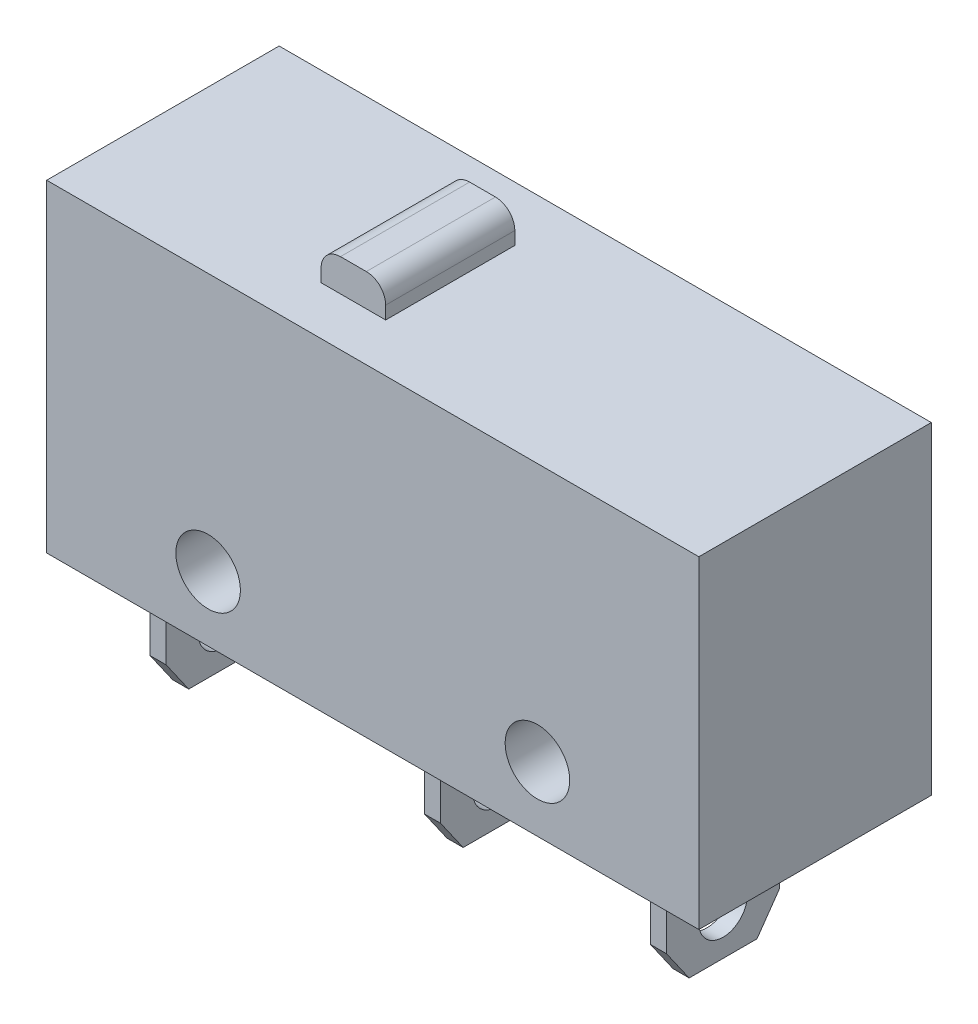
SolidWorks part; units mm, degrees
ref_plane "Спереди" through (0, 0, 0) normal (0, 0, 1) x (1, 0, 0)
ref_plane "Сверху" through (0, 0, 0) normal (0, 1, 0) x (1, 0, 0)
ref_plane "Справа" through (0, 0, 0) normal (1, 0, 0) x (0, 0, -1)
sketch "Эскиз1" plane through (0, 0, 0) normal (0, 1, 0) x (1, 0, 0)
  line L1 (-10.1, 3.6) -> (10.1, 3.6)
  line L2 (-10.1, 3.6) -> (-10.1, -3.6)
  line L3 (-10.1, -3.6) -> (10.1, -3.6)
  line L4 (10.1, 3.6) -> (10.1, -3.6)
  line L5 (-10.1, 3.6) -> (10.1, -3.6) construction
  line L6 (-10.1, -3.6) -> (10.1, 3.6) construction
  point P0 (0, 0)
  dimension "D1" = 20.2
  dimension "D2" = 7.2
extrude "Бобышка-Вытянуть1" add sketch "Эскиз1" along normal blind 10
sketch "Эскиз2" plane through (0, 0, 0) normal (0, -1, 0) x (-1, 0, 0)
  line L0 (-6.75, -1.75) -> (-6.75, 1.75)
  line L1 (0.25, -1.75) -> (-0.25, -1.75)
  line L2 (0.25, -1.75) -> (0.25, 1.75)
  line L3 (0.25, 1.75) -> (-0.25, 1.75)
  line L4 (-0.25, -1.75) -> (-0.25, 1.75)
  line L5 (0.25, -1.75) -> (-0.25, 1.75) construction
  line L6 (0.25, 1.75) -> (-0.25, -1.75) construction
  line L7 (-7.25, -1.75) -> (-7.25, 1.75)
  line L8 (-6.75, -1.75) -> (-7.25, -1.75)
  line L9 (-6.75, 1.75) -> (-7.25, 1.75)
  line L10 (8.75, -1.75) -> (8.75, 1.75)
  line L11 (8.75, -1.75) -> (8.25, -1.75)
  line L12 (8.25, -1.75) -> (8.25, 1.75)
  line L13 (8.75, 1.75) -> (8.25, 1.75)
  point P0 (0, 0)
  dimension "D1" = 3.5
  dimension "D2" = 0.5
  dimension "D3" = 2
  dimension "D4" = 2
extrude "Бобышка-Вытянуть2" add sketch "Эскиз2" along normal blind 4
sketch "Эскиз3" plane through (-8.75, 0, 0) normal (-1, 0, 0) x (0, 0, 1)
  circle A0 centre (0, -2.6809) radius 0.75
  dimension "D1" = 1.5
extrude "Вырез-Вытянуть1" cut sketch "Эскиз3" against normal up to surface (16 mm away) up to face at (7.25, -2, 0)
chamfer "Фаска1" distance 1 angle 35 6 edges at (7, -4, -1.75) (7, -4, 1.75) (0, -4, 1.75) (0, -4, -1.75) (-8.5, -4, -1.75) (-8.5, -4, 1.75)
sketch "Эскиз4" plane through (0, 0, -3.6) normal (0, 0, -1) x (-1, 0, 0)
  line L0 (0, 10) -> (0, 0) construction
  line L1 (-10.1, 10) -> (10.1, 10) construction
  line L2 (-10.1, 10) -> (-10.1, 0) construction
  line L3 (-10.1, 0) -> (10.1, 0) construction
  circle A0 centre (-5.1, 2) radius 1
  circle A1 centre (5.1, 2) radius 1
  dimension "D1" = 2
  dimension "D2" = 5
  dimension "D3" = 2
extrude "Вырез-Вытянуть2" cut sketch "Эскиз4" against normal through all
sketch "Эскиз5" plane through (0, 10, 0) normal (0, 1, 0) x (1, 0, 0)
  line L0 (-10.1, 3.6) -> (-10.1, -3.6) construction
  line L1 (-3.1, -2.1) -> (-1.1, -2.1)
  line L2 (-3.1, -2.1) -> (-3.1, 1.9)
  line L3 (-3.1, 1.9) -> (-1.1, 1.9)
  line L4 (-1.1, -2.1) -> (-1.1, 1.9)
  line L5 (-10.1, 0) -> (10.1, 0) construction
  line L6 (10.1, -3.6) -> (10.1, 3.6) construction
  line L7 (-10.1, -3.6) -> (10.1, -3.6) construction
  dimension "D1" = 7
  dimension "D2" = 4
  dimension "D3" = 2
  dimension "D4" = 1.5
extrude "Бобышка-Вытянуть3" add sketch "Эскиз5" along normal blind 1
fillet "Скругление1" radius 0.6 2 edges at (-1.1, 11, 0.1) (-3.1, 11, 0.1)
